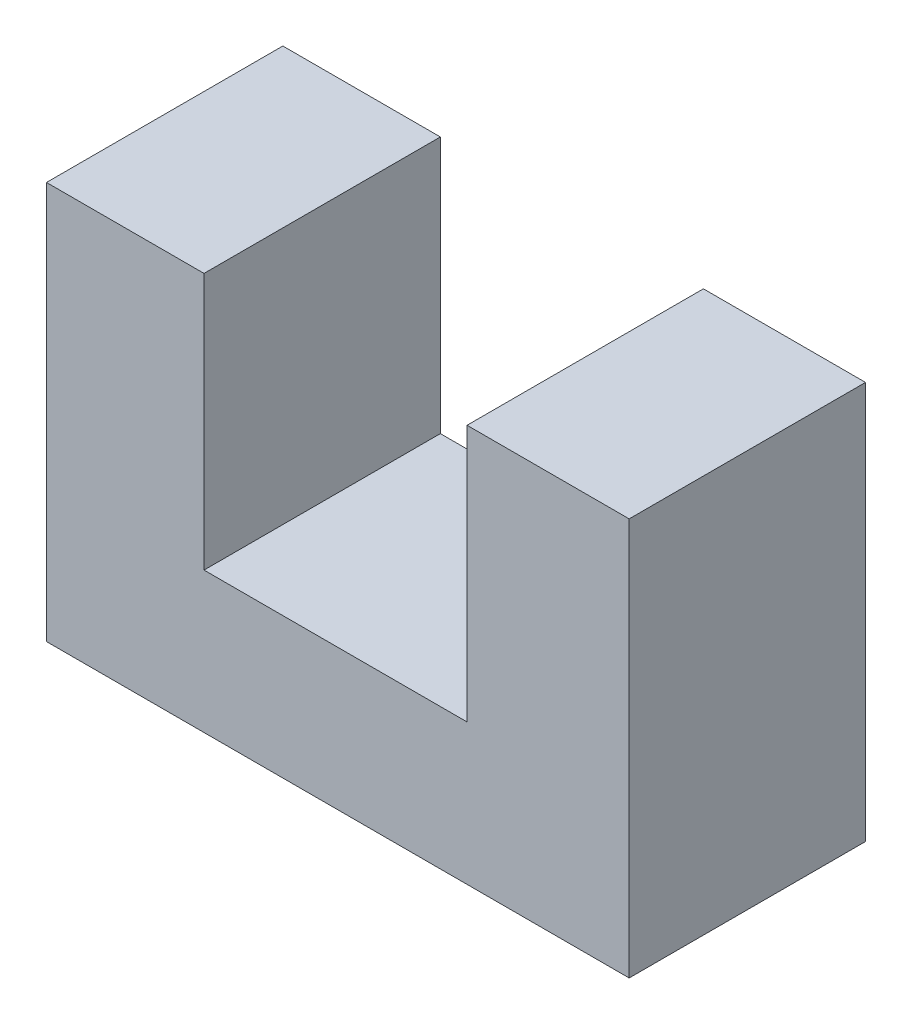
SolidWorks part; units mm, degrees
ref_plane "Front Plane" through (0, 0, 0) normal (0, 0, 1) x (1, 0, 0)
ref_plane "Top Plane" through (0, 0, 0) normal (0, 1, 0) x (1, 0, 0)
ref_plane "Right Plane" through (0, 0, 0) normal (1, 0, 0) x (0, 0, -1)
other "Configuration Table"
sketch "Sketch1" plane through (0, 0, 0) normal (0, 0, 1) x (1, 0, 0)
  line L0 (0, 0) -> (69.5102, 0)
  line L1 (69.5102, 0) -> (69.5102, 47.4348)
  line L2 (69.5102, 47.4348) -> (50.1714, 47.4348)
  line L3 (50.1714, 47.4348) -> (50.1714, 16.7846)
  line L4 (50.1714, 16.7846) -> (18.7915, 16.7846)
  line L5 (18.7915, 16.7846) -> (18.7915, 47.4348)
  line L6 (18.7915, 47.4348) -> (0, 47.4348)
  line L7 (0, 47.4348) -> (0, 0)
extrude "Boss-Extrude1" add sketch "Sketch1" along normal blind 28.194
